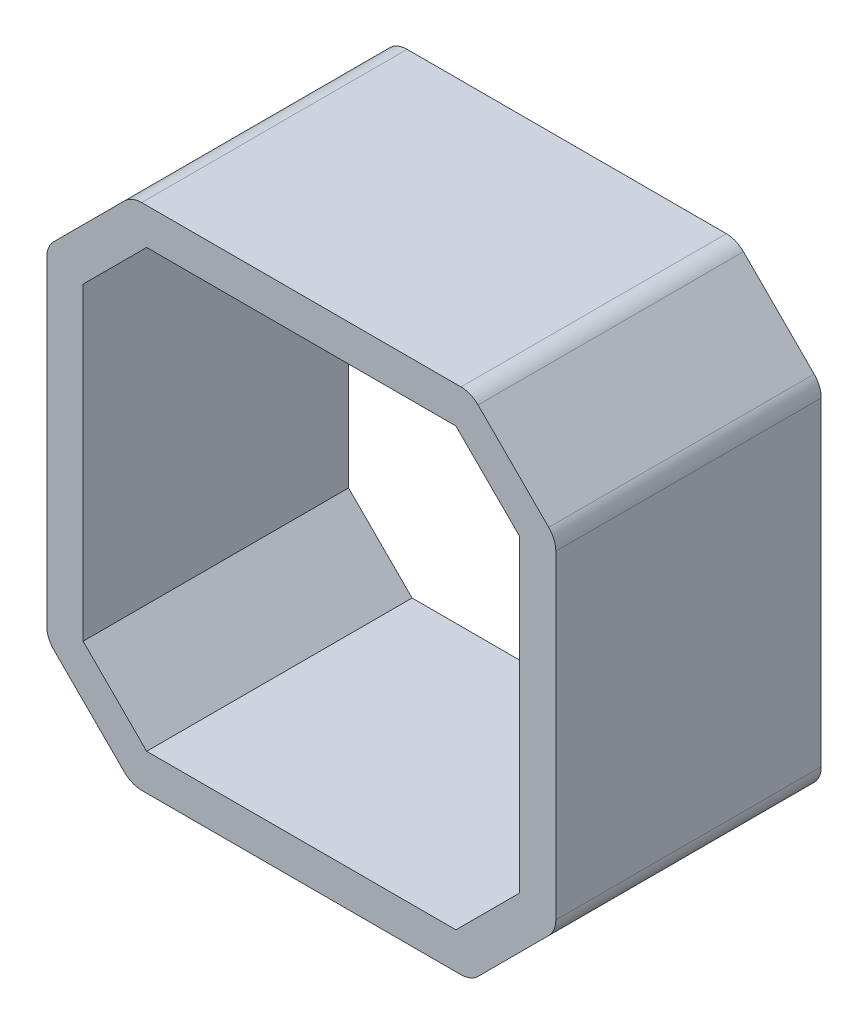
SolidWorks part; units mm, degrees
ref_plane "Front Plane" through (0, 0, 0) normal (0, 0, 1) x (1, 0, 0)
ref_plane "Top Plane" through (0, 0, 0) normal (0, 1, 0) x (1, 0, 0)
ref_plane "Right Plane" through (0, 0, 0) normal (1, 0, 0) x (0, 0, -1)
sketch "Sketch1" plane through (0, 0, 0) normal (0, 0, 1) x (1, 0, 0)
  line L1 (-21, 21) -> (21, 21)
  line L2 (-21, 21) -> (-21, -21)
  line L3 (-21, -21) -> (21, -21)
  line L4 (21, 21) -> (21, -21)
  line L5 (-21, 21) -> (21, -21) construction
  line L6 (-21, -21) -> (21, 21) construction
  point P0 (0, 0)
  dimension "D1" = 42
  dimension "D2" = 42
extrude "Boss-Extrude1" add sketch "Sketch1" along normal mid plane 21.9
sketch "Sketch2" plane through (0, 0, 10.95) normal (0, 0, 1) x (1, 0, 0)
  line L0 (-9.4281, 0) -> (10.8566, 0) construction
  line L1 (0, 9.6067) -> (0, -6.964) construction
  line L2 (-21, 21) -> (-21, 14)
  line L3 (-21, 21) -> (-21, -21) construction
  line L4 (-21, 21) -> (-14, 21)
  line L5 (21, 21) -> (-21, 21) construction
  line L6 (-21, 14) -> (-14, 21)
  line L7 (-21, -14) -> (-14, -21)
  line L8 (-21, -21) -> (-14, -21)
  line L9 (-21, -21) -> (-21, -14)
  line L10 (21, -21) -> (21, -14)
  line L11 (21, -21) -> (14, -21)
  line L12 (21, -14) -> (14, -21)
  line L13 (21, 14) -> (14, 21)
  line L14 (21, 21) -> (14, 21)
  line L15 (21, 21) -> (21, 14)
  dimension "D1" = 7
  dimension "D2" = 7
extrude "Cut-Extrude1" cut sketch "Sketch2" against normal up to next
fillet "Fillet1" radius 2 8 edges at (14, 21, 0) (21, 14, 0) (21, -14, 0) (14, -21, 0) (-14, -21, 0) (-21, -14, 0) (-21, 14, 0) (-14, 21, 0)
sketch3d "3DSketch1"
  line L0 (12.7574, -18, 10.95) -> (18, -12.7574, 10.95)
  line L1 (18, -12.7574, 10.95) -> (18, 12.7574, 10.95)
  line L2 (18, 12.7574, 10.95) -> (12.7574, 18, 10.95)
  line L3 (12.7574, 18, 10.95) -> (-12.7574, 18, 10.95)
  line L4 (-12.7574, 18, 10.95) -> (-18, 12.7574, 10.95)
  line L5 (-18, 12.7574, 10.95) -> (-18, -12.7574, 10.95)
  line L6 (-18, -12.7574, 10.95) -> (-12.7574, -18, 10.95)
  line L7 (-12.7574, -18, 10.95) -> (12.7574, -18, 10.95)
  line L8 (12.7574, -18, 10.95) -> (18, -12.7574, 10.95)
  line L9 (18, -12.7574, 10.95) -> (18, 12.7574, 10.95)
  line L10 (18, 12.7574, 10.95) -> (12.7574, 18, 10.95)
  line L11 (12.7574, 18, 10.95) -> (-12.7574, 18, 10.95)
  line L12 (-12.7574, 18, 10.95) -> (-18, 12.7574, 10.95)
  line L13 (-18, 12.7574, 10.95) -> (-18, -12.7574, 10.95)
  line L14 (-18, -12.7574, 10.95) -> (-12.7574, -18, 10.95)
  line L15 (-12.7574, -18, 10.95) -> (12.7574, -18, 10.95)
  dimension "D1" = 3
extrude "Cut-Extrude2" cut sketch "3DSketch1" along a picked direction on the side against the normal up to next (21.9 mm away)
